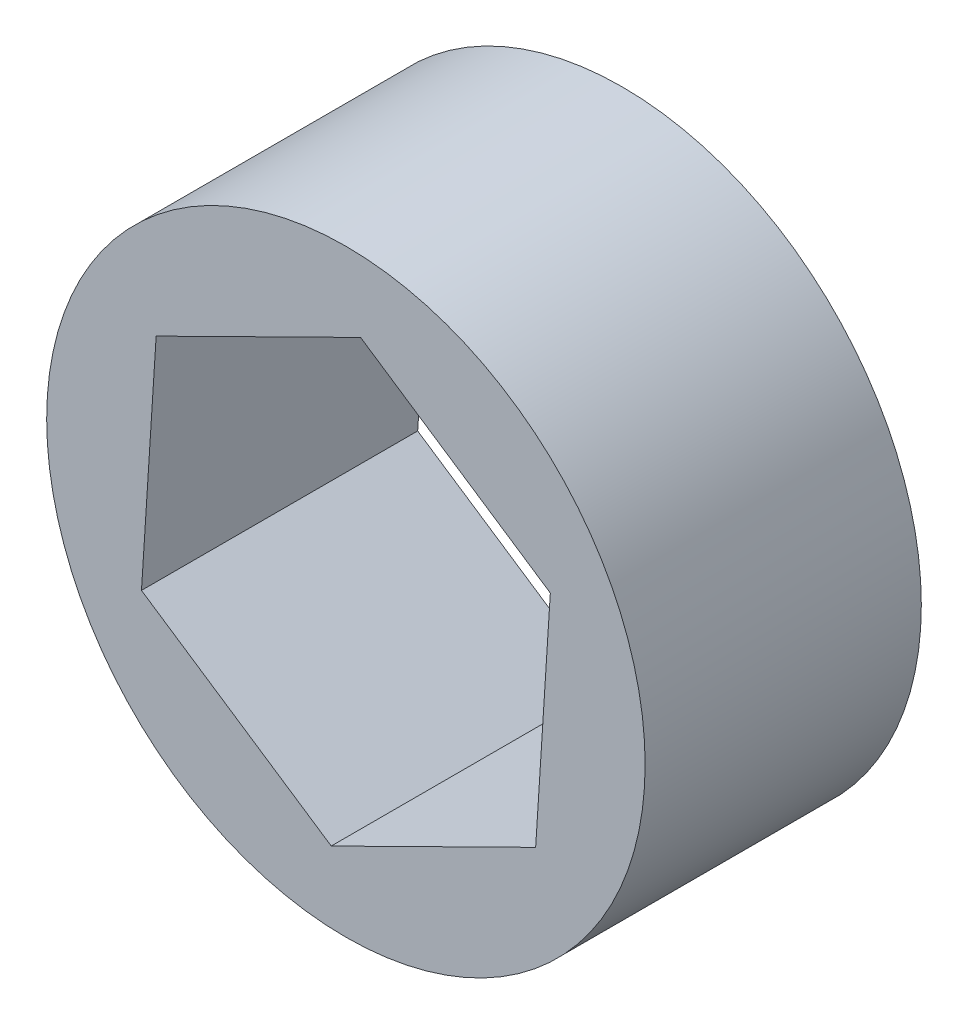
SolidWorks part; units mm, degrees
ref_plane "Front Plane" through (0, 0, 0) normal (0, 0, 1) x (1, 0, 0)
ref_plane "Top Plane" through (0, 0, 0) normal (0, 1, 0) x (1, 0, 0)
ref_plane "Right Plane" through (0, 0, 0) normal (1, 0, 0) x (0, 0, -1)
sketch "Sketch1" plane through (0, 0, 0) normal (0, 0, 1) x (1, 0, 0)
  line L1 (-6.3411, 4.2274) -> (-6.8316, -3.3778)
  line L2 (-6.8316, -3.3778) -> (-0.4905, -7.6052)
  line L3 (-0.4905, -7.6052) -> (6.3411, -4.2274)
  line L4 (6.3411, -4.2274) -> (6.8316, 3.3778)
  line L5 (6.8316, 3.3778) -> (0.4905, 7.6052)
  line L6 (0.4905, 7.6052) -> (-6.3411, 4.2274)
  circle A0 centre (0, 0) radius 6.6 construction
  circle A1 centre (0, 0) radius 10
  dimension "D1" = 13.2
  dimension "D2" = 20
extrude "Boss-Extrude1" add sketch "Sketch1" along normal blind 9.23
